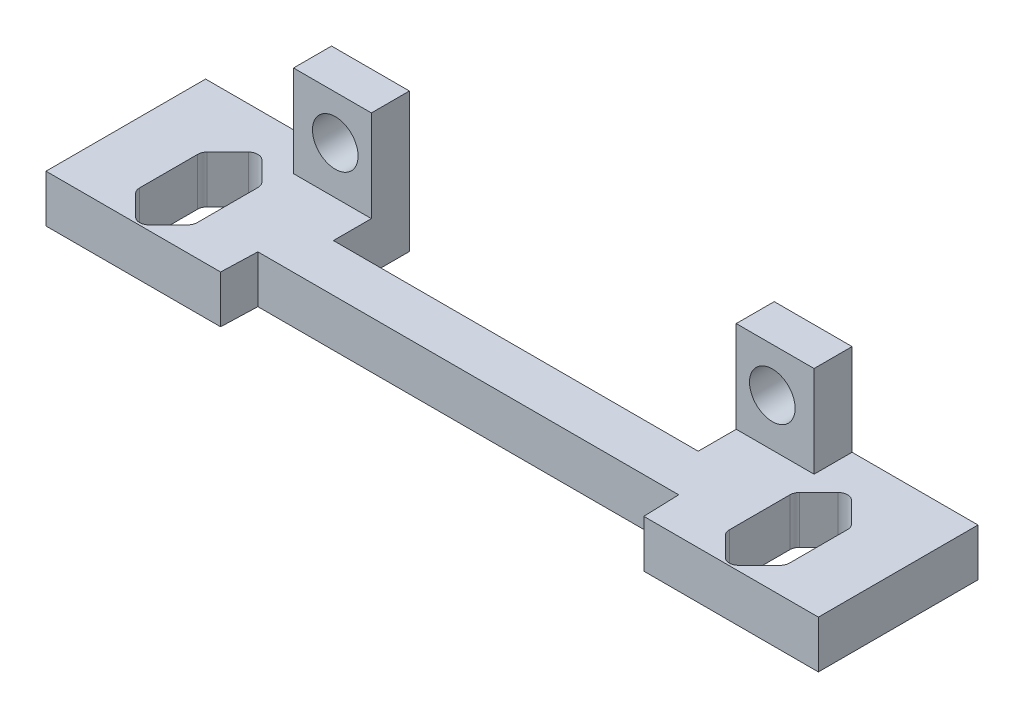
SolidWorks part; units mm, degrees
ref_plane "前视基准面" through (0, 0, 0) normal (0, 0, 1) x (1, 0, 0)
ref_plane "上视基准面" through (0, 0, 0) normal (0, 1, 0) x (1, 0, 0)
ref_plane "右视基准面" through (0, 0, 0) normal (1, 0, 0) x (0, 0, -1)
sketch "参考面" plane through (0, 0, 0) normal (0, 1, 0) x (1, 0, 0)
  line L0 (0, 17.1678) -> (0, -7.9399) construction
  line L1 (-14.1474, -13.5693) -> (-15.2326, -12.4841)
  line L2 (-15.9397, -12.4841) -> (-16.9545, -13.499)
  line L3 (-11.3955, -31.9433) -> (-10.3849, -1.2232)
  line L4 (-10.5767, -38.0268) -> (-5.85, -43.5)
  line L5 (-5.85, -43.5) -> (5.85, -43.5)
  line L6 (-11.3974, -35.8209) -> (-11.3974, -32.0543)
  line L7 (-9.5, 0) -> (9.5, 0)
  line L8 (10.5767, -38.0268) -> (5.85, -43.5)
  line L9 (11.3974, -35.8209) -> (11.3974, -32.0543)
  line L10 (11.3955, -31.9433) -> (10.3849, -1.2232)
  line L11 (-16.9545, -22.7061) -> (-15.8693, -23.7913)
  line L12 (-15.1622, -23.7913) -> (-14.1474, -22.7764)
  line L13 (-17.1009, -13.8525) -> (-17.1009, -22.3525)
  line L14 (-14.0009, -13.9229) -> (-14.0009, -16.9775)
  line L15 (-14.0009, -16.9775) -> (-14.5009, -17.4775)
  line L16 (-14.5009, -17.4775) -> (-14.5009, -18.7275)
  line L17 (-14.5009, -18.7275) -> (-14.0009, -19.2275)
  line L18 (-14.0009, -19.2275) -> (-14.0009, -22.4229)
  line L19 (14.5009, -18.7275) -> (14.0009, -19.2275)
  line L20 (14.5009, -17.4775) -> (14.5009, -18.7275)
  line L21 (14.0009, -16.9775) -> (14.5009, -17.4775)
  line L22 (14.0009, -13.9229) -> (14.0009, -16.9775)
  line L23 (14.1474, -13.5693) -> (15.2326, -12.4841)
  line L24 (15.9397, -12.4841) -> (16.9545, -13.499)
  line L25 (17.1009, -13.8525) -> (17.1009, -22.3525)
  line L26 (16.9545, -22.7061) -> (15.8693, -23.7913)
  line L27 (15.1622, -23.7913) -> (14.1474, -22.7764)
  line L28 (14.0009, -19.2275) -> (14.0009, -22.4229)
  arc A0 (-14.0009, -13.9229) -> (-14.1474, -13.5693) centre (-14.5009, -13.9229) ccw
  arc A1 (-15.2326, -12.4841) -> (-15.9397, -12.4841) centre (-15.5861, -12.8377) ccw
  arc A2 (-17.1009, -13.8525) -> (-16.9545, -13.499) centre (-16.6009, -13.8525) cw
  arc A3 (-9.5, 0) -> (-10.3849, -1.2232) centre (-9.0356, -1.2676) ccw
  arc A4 (-11.3974, -32.0543) -> (-11.3955, -31.9433) centre (-8.0224, -32.0543) cw
  arc A5 (-10.5767, -38.0268) -> (-11.3974, -35.8209) centre (-8.0224, -35.8209) cw
  arc A6 (10.5767, -38.0268) -> (11.3974, -35.8209) centre (8.0224, -35.8209) ccw
  arc A7 (11.3974, -32.0543) -> (11.3955, -31.9433) centre (8.0224, -32.0543) ccw
  arc A8 (9.5, 0) -> (10.3849, -1.2232) centre (9.0356, -1.2676) cw
  arc A9 (-17.1009, -22.3525) -> (-16.9545, -22.7061) centre (-16.6009, -22.3525) ccw
  arc A10 (-15.8693, -23.7913) -> (-15.1622, -23.7913) centre (-15.5157, -23.4377) ccw
  arc A11 (-14.0009, -22.4229) -> (-14.1474, -22.7764) centre (-14.5009, -22.4229) cw
  arc A12 (14.0009, -13.9229) -> (14.1474, -13.5693) centre (14.5009, -13.9229) cw
  arc A13 (15.2326, -12.4841) -> (15.9397, -12.4841) centre (15.5861, -12.8377) cw
  arc A14 (17.1009, -13.8525) -> (16.9545, -13.499) centre (16.6009, -13.8525) ccw
  arc A15 (17.1009, -22.3525) -> (16.9545, -22.7061) centre (16.6009, -22.3525) cw
  arc A16 (15.8693, -23.7913) -> (15.1622, -23.7913) centre (15.5157, -23.4377) cw
  arc A17 (14.0009, -22.4229) -> (14.1474, -22.7764) centre (14.5009, -22.4229) ccw
  point P32 (-11.0823, -22.4229)
  point P49 (0, -43.5)
  point P58 (0, 0)
sketch "草图2" plane through (0, 0, 0) normal (0, 1, 0) x (1, 0, 0)
  line L2 (11.3955, -31.9433) -> (10.3849, -1.2232) construction
  line L4 (11.1361, -24.0562) -> (20.3239, -24.0562)
  line L11 (14.0009, -19.2275) -> (14.0009, -22.4229)
  line L12 (14.1474, -22.7764) -> (15.1622, -23.7913)
  line L13 (16.9545, -22.7061) -> (15.8693, -23.7913)
  line L15 (-11.1361, -24.0562) -> (-20.3239, -24.0562)
  line L21 (0, 2.8472) -> (0, -12.4841) construction
  line L22 (0, 17.1678) -> (0, -7.9399) construction
  line L26 (16.9545, -18.9443) -> (15.8693, -17.8591)
  line L30 (-14.0009, -19.2275) -> (-14.0009, -22.4229)
  line L34 (-16.9545, -22.7061) -> (-15.8693, -23.7913)
  line L35 (-14.1474, -22.7764) -> (-15.1622, -23.7913)
  line L36 (-10.8621, -15.6567) -> (-9.6, -15.6567)
  line L37 (-9.6, -15.6567) -> (-9.6, -22.1567)
  line L38 (-9.6, -22.1567) -> (-11.0736, -22.1567)
  line L39 (9.6, -22.1567) -> (11.0736, -22.1567)
  line L40 (9.6, -15.6567) -> (9.6, -22.1567)
  line L41 (10.8621, -15.6567) -> (9.6, -15.6567)
  line L42 (-11.0736, -22.1567) -> (-11.1361, -24.0562)
  line L43 (11.0736, -22.1567) -> (11.1361, -24.0562)
  line L44 (-10.8621, -15.6567) -> (-14.0009, -15.6567)
  line L45 (-17.1009, -15.6567) -> (-20.3239, -15.6567)
  line L46 (-20.3239, -24.0562) -> (-20.3239, -15.6567)
  line L49 (10.8621, -15.6567) -> (14.0009, -15.6567)
  line L50 (20.3239, -15.6567) -> (17.1009, -15.6567)
  line L51 (20.3239, -15.6567) -> (20.3239, -24.0562)
  line L54 (-17.1009, -22.3525) -> (-17.1009, -19.2979)
  line L55 (-17.1009, -13.8525) -> (-17.1009, -22.3525) construction
  line L56 (-17.531, -20.8252) -> (-12.875, -20.8252) construction
  line L57 (-14.1474, -18.874) -> (-15.1622, -17.8591)
  line L58 (-16.9545, -18.9443) -> (-15.8693, -17.8591)
  line L59 (-17.1009, -15.6567) -> (-14.0009, -15.6567)
  line L60 (17.5016, -20.8252) -> (13.274, -20.8252) construction
  line L61 (14.1474, -18.874) -> (15.1622, -17.8591)
  line L62 (17.1009, -19.2979) -> (17.1009, -22.3525)
  line L63 (14.0009, -15.6567) -> (17.1009, -15.6567)
  arc A0 (14.0009, -22.4229) -> (14.1474, -22.7764) centre (14.5009, -22.4229) ccw
  arc A1 (15.1622, -23.7913) -> (15.8693, -23.7913) centre (15.5157, -23.4377) ccw
  arc A2 (17.1009, -22.3525) -> (16.9545, -22.7061) centre (16.6009, -22.3525) cw
  arc A9 (-17.1009, -22.3525) -> (-16.9545, -22.7061) centre (-16.6009, -22.3525) ccw
  arc A10 (-15.8693, -23.7913) -> (-15.1622, -23.7913) centre (-15.5157, -23.4377) ccw
  arc A11 (-14.0009, -22.4229) -> (-14.1474, -22.7764) centre (-14.5009, -22.4229) cw
  arc A12 (-15.8693, -17.8591) -> (-15.1622, -17.8591) centre (-15.5157, -18.2127) cw
  arc A13 (-14.0009, -19.2275) -> (-14.1474, -18.874) centre (-14.5009, -19.2275) ccw
  arc A14 (-17.1009, -19.2979) -> (-16.9545, -18.9443) centre (-16.6009, -19.2979) cw
  arc A15 (17.1009, -19.2979) -> (16.9545, -18.9443) centre (16.6009, -19.2979) ccw
  arc A16 (15.1622, -17.8591) -> (15.8693, -17.8591) centre (15.5157, -18.2127) cw
  arc A17 (14.0009, -19.2275) -> (14.1474, -18.874) centre (14.5009, -19.2275) cw
  dimension "D1" = 19.2
  dimension "D2" = 6.5
extrude "连接件固定位" add sketch "草图2" along normal blind 2.5
sketch "草图3" plane through (0, 0, 15.6567) normal (0, 0, -1) x (-1, 0, 0)
  line L0 (0, 6.8267) -> (0, -3.5616) construction
  line L1 (-9.6, 2.5) -> (-13.6968, 2.5)
  line L2 (-9.6, 2.5) -> (-9.6, 7.3177)
  line L3 (-9.6, 7.3177) -> (-13.6968, 7.3177)
  line L4 (-13.6968, 2.5) -> (-13.6968, 7.3177)
  line L5 (9.6, 7.3177) -> (13.6968, 7.3177)
  line L6 (13.6968, 2.5) -> (13.6968, 7.3177)
  line L7 (9.6, 2.5) -> (13.6968, 2.5)
  line L8 (9.6, 2.5) -> (9.6, 7.3177)
  circle A0 centre (-11.5, 5) radius 1.2
  circle A1 centre (11.5, 5) radius 1.2
  dimension "D1" = 2.4
  dimension "D2" = 23
  dimension "D3" = 2.5
extrude "凸台-拉伸1" add sketch "草图3" against normal blind 2
sketch "草图5" plane through (9.6, 0, 0) normal (-1, 0, 0) x (0, 0, 1)
  line L0 (17.6567, 2.5) -> (22.1567, 2.5) construction
  line L1 (22.1567, 0) -> (19.6567, 0)
  line L2 (22.1567, 0) -> (22.1567, 2.5)
  line L3 (22.1567, 2.5) -> (19.6567, 2.5)
  line L4 (19.6567, 0) -> (19.6567, 2.5)
  line L5 (17.6567, 2.5) -> (17.6567, 7.3177) construction
  dimension "D1" = 2
extrude "凸台-拉伸2" add sketch "草图5" along normal up to next
sketch "草图7" plane through (0, 0, 0) normal (0, -1, 0) x (1, 0, 0)
  line L0 (17.1009, 20.8252) -> (-17.1009, 20.8252) construction
  line L1 (17.1009, 22.3525) -> (17.1009, 19.2979) construction
  line L2 (-17.1009, 19.2979) -> (-17.1009, 22.3525) construction
  line L3 (15.5157, 17.8311) -> (15.5157, 24.0065) construction
  line L4 (-15.5157, 17.7127) -> (-15.5157, 23.919) construction
  arc A0 (-15.8693, 17.8591) -> (-15.1622, 17.8591) centre (-15.5157, 18.2127) ccw construction
